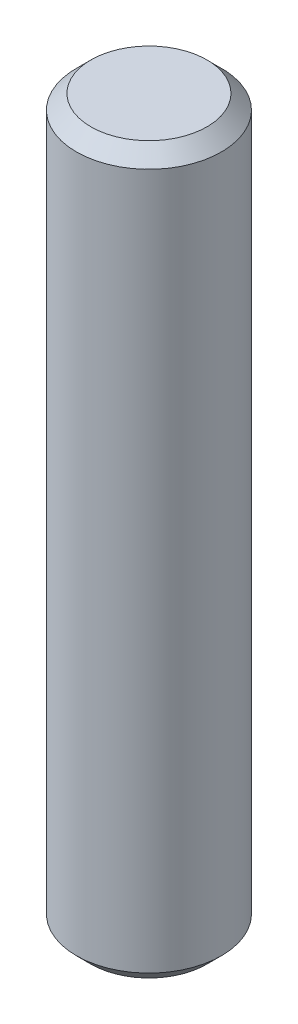
SolidWorks part; units mm, degrees
ref_plane "Front Plane" through (0, 0, 0) normal (0, 0, 1) x (1, 0, 0)
ref_plane "Top Plane" through (0, 0, 0) normal (0, 1, 0) x (1, 0, 0)
ref_plane "Right Plane" through (0, 0, 0) normal (1, 0, 0) x (0, 0, -1)
sketch "Sketch1" plane through (0, 0, 0) normal (0, 1, 0) x (1, 0, 0)
  circle A0 centre (0, 0) radius 5
  dimension "D1" = 10
extrude "Corpo" add sketch "Sketch1" along normal blind 50
chamfer "Chanfro 1×45°" distance 1 angle 45 2 edges at (0, 0, 5) (0, 50, 5)
